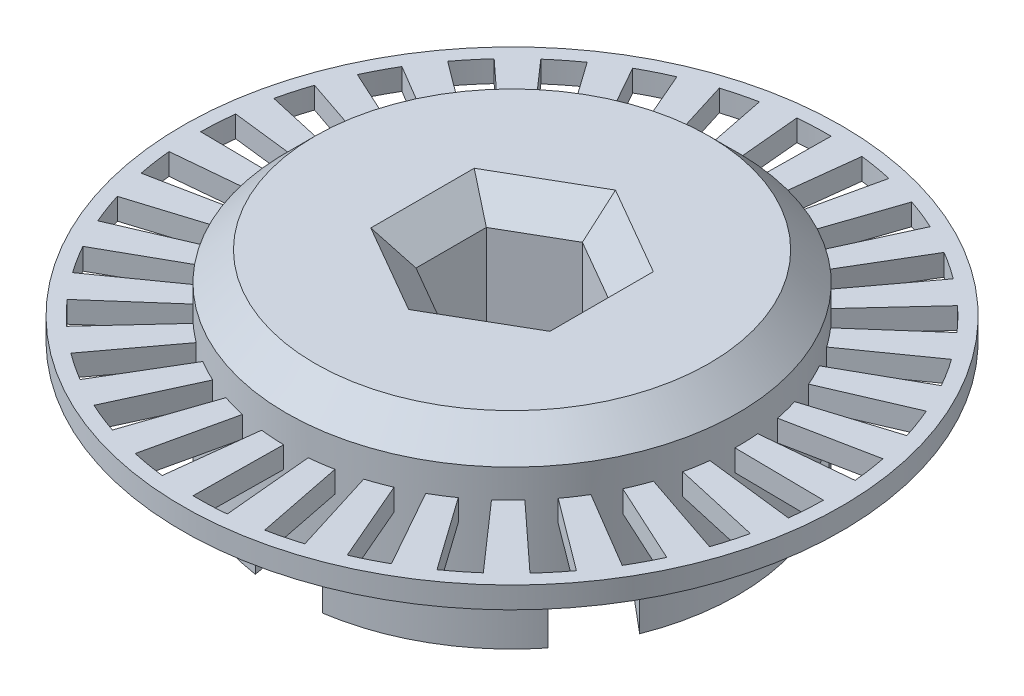
SolidWorks part; units mm, degrees
ref_plane "Front Plane" through (0, 0, 0) normal (0, 0, 1) x (1, 0, 0)
ref_plane "Top Plane" through (0, 0, 0) normal (0, 1, 0) x (1, 0, 0)
ref_plane "Right Plane" through (0, 0, 0) normal (1, 0, 0) x (0, 0, -1)
sketch "Sketch1" plane through (0, 0, 0) normal (0, 1, 0) x (1, 0, 0)
  circle A0 centre (0, 0) radius 15.75
  dimension "D1" = 31.5
extrude "Boss-Extrude1" add sketch "Sketch1" along normal blind 10
sketch "Sketch2" plane through (0, 10, 0) normal (0, 1, 0) x (1, 0, 0)
  line L0 (0, -5.5) -> (0, 5.5) construction
  line L1 (4.25, 2.4537) -> (0, 4.9075)
  line L2 (0, 4.9075) -> (-4.25, 2.4537)
  line L3 (-4.25, 2.4537) -> (-4.25, -2.4537)
  line L4 (-4.25, -2.4537) -> (0, -4.9075)
  line L5 (0, -4.9075) -> (4.25, -2.4537)
  line L6 (4.25, -2.4537) -> (4.25, 2.4537)
  circle A0 centre (0, 0) radius 4.25 construction
  dimension "D1" = 8.5
extrude "Cut-Extrude1" cut sketch "Sketch2" against normal blind 10
sketch "Sketch3" plane through (0, 0, 0) normal (0, -1, 0) x (1, 0, 0)
  line L0 (0, 0) -> (-43301.2702, -25000) construction
  line L1 (0, 0) -> (0, 50000) construction
  line L2 (0, 0) -> (43301.2702, -25000) construction
  line L3 (0, 0) -> (-50000, 0) construction
  line L4 (0, 0) -> (-7.8, 0) construction
  line L5 (-7.8, 0) -> (-38310.0222, -32139.3805) construction
  line L6 (-7.8, 0) -> (-38310.0222, 32139.3805) construction
  line L7 (-7.8, 0) -> (-14.6603, -5.7565)
  line L8 (-7.8, 0) -> (-14.6603, 5.7565)
  line L9 (-3.9, 6.755) -> (-12.3154, 9.818)
  line L10 (-3.9, 6.755) -> (-2.3449, 15.5745)
  line L11 (3.9, 6.755) -> (2.3449, 15.5745)
  line L12 (3.9, 6.755) -> (12.3154, 9.818)
  line L13 (7.8, 0) -> (14.6603, 5.7565)
  line L14 (7.8, 0) -> (14.6603, -5.7565)
  line L15 (3.9, -6.755) -> (12.3154, -9.818)
  line L16 (3.9, -6.755) -> (2.3449, -15.5745)
  line L17 (-3.9, -6.755) -> (-2.3449, -15.5745)
  line L18 (-3.9, -6.755) -> (-12.3154, -9.818)
  line L21 (5.5, 0) -> (-5.5, 0) construction
  circle A0 centre (0, 0) radius 15.75 construction
  arc A1 (-14.6603, 5.7565) -> (-14.6603, -5.7565) centre (0, 0) ccw
  arc A2 (-2.3449, 15.5745) -> (-12.3154, 9.818) centre (0, 0) ccw
  arc A3 (12.3154, 9.818) -> (2.3449, 15.5745) centre (0, 0) ccw
  arc A4 (14.6603, -5.7565) -> (14.6603, 5.7565) centre (0, 0) ccw
  arc A5 (2.3449, -15.5745) -> (12.3154, -9.818) centre (0, 0) ccw
  arc A6 (-12.3154, -9.818) -> (-2.3449, -15.5745) centre (0, 0) ccw
  point P43 (0, 0)
  circle M10 centre (0, 0) radius 15.75
  dimension "D1" = 60
  dimension "D2" = 60
  dimension "D3" = 30
  dimension "D4" = 7.8
  dimension "D5" = 40
  dimension "D6" = 40
  dimension "D7" = 6
extrude "Boss-Extrude2" add sketch "Sketch3" along normal blind 3 contours L7 L8 M10 | L17 L18 M10 | L15 L16 M10 | L13 L14 M10 | L11 L12 M10 | L9 L10 M10
sketch "Sketch4" plane through (0, 10, 0) normal (0, 1, 0) x (1, 0, 0)
  circle A0 centre (0, 0) radius 7.1
  dimension "D1" = 14.2
extrude "Cut-Extrude2" [suppressed] cut sketch "Sketch4" against normal blind 3
chamfer "Chamfer1" distance 2 angle 45 7 edges at (0, 10, 15.75) (2.125, 10, -3.6806) (-2.125, 10, -3.6806) (-4.25, 10, 0) (-2.125, 10, 3.6806) (2.125, 10, 3.6806) (4.25, 10, 0)
sketch3d "3DSketch2" plane through (0, 0, 0) normal (0, 0, 1) x (1, 0, 0)
  dimension "D1" = 6
sketch "Sketch5" plane through (0, 6, 0) normal (0, -1, 0) x (-1, 0, 0)
  line L0 (0, 0) -> (49030.2577, -9799.6852) construction
  line L1 (0, 0) -> (49786.0108, -4620.944) construction
  line L2 (0, 0) -> (49996.2981, 608.4252) construction
  line L3 (21.5733, -4.3119) -> (15.4445, -3.0869)
  line L4 (21.9058, -2.0332) -> (15.6826, -1.4556)
  line L5 (20.2054, -8.703) -> (14.4652, -6.2305)
  line L6 (21.0044, -6.5433) -> (15.0373, -4.6844)
  line L7 (17.9544, -12.7137) -> (12.8537, -9.1019)
  line L8 (19.185, -10.7673) -> (13.7347, -7.7084)
  line L9 (14.9187, -16.1688) -> (10.6805, -11.5754)
  line L10 (16.5271, -14.5208) -> (11.8319, -10.3956)
  line L11 (11.231, -18.9173) -> (8.0404, -13.5431)
  line L12 (13.1469, -17.6397) -> (9.412, -12.6284)
  line L13 (7.0525, -20.839) -> (5.0489, -14.9188)
  line L14 (9.1921, -19.9876) -> (6.5807, -14.3093)
  line L15 (2.5657, -21.8499) -> (1.8368, -15.6425)
  line L16 (4.8356, -21.462) -> (3.4618, -15.3648)
  line L17 (-2.0332, -21.9058) -> (-1.4556, -15.6826)
  line L18 (0.2677, -21.9984) -> (0.1917, -15.7488)
  line L19 (-6.5433, -21.0044) -> (-4.6844, -15.0373)
  line L20 (-4.3119, -21.5733) -> (-3.0869, -15.4445)
  line L21 (-10.7673, -19.185) -> (-7.7084, -13.7347)
  line L22 (-8.703, -20.2054) -> (-6.2305, -14.4652)
  line L23 (-14.5208, -16.5271) -> (-10.3956, -11.8319)
  line L24 (-12.7137, -17.9544) -> (-9.1019, -12.8537)
  line L25 (-17.6397, -13.1469) -> (-12.6284, -9.412)
  line L26 (-16.1688, -14.9187) -> (-11.5754, -10.6805)
  line L27 (-19.9876, -9.1921) -> (-14.3093, -6.5807)
  line L28 (-18.9173, -11.231) -> (-13.5431, -8.0404)
  line L29 (-21.462, -4.8356) -> (-15.3648, -3.4618)
  line L30 (-20.839, -7.0525) -> (-14.9188, -5.0489)
  line L31 (-21.9984, -0.2677) -> (-15.7488, -0.1917)
  line L32 (-21.8499, -2.5657) -> (-15.6425, -1.8368)
  line L33 (-21.5733, 4.3119) -> (-15.4445, 3.0869)
  line L34 (-21.9058, 2.0332) -> (-15.6826, 1.4556)
  line L35 (-20.2054, 8.703) -> (-14.4652, 6.2305)
  line L36 (-21.0044, 6.5433) -> (-15.0373, 4.6844)
  line L37 (-17.9544, 12.7137) -> (-12.8537, 9.1019)
  line L38 (-19.185, 10.7673) -> (-13.7347, 7.7084)
  line L39 (-14.9187, 16.1688) -> (-10.6805, 11.5754)
  line L40 (-16.5271, 14.5208) -> (-11.8319, 10.3956)
  line L41 (-11.231, 18.9173) -> (-8.0404, 13.5431)
  line L42 (-13.1469, 17.6397) -> (-9.412, 12.6284)
  line L43 (-7.0525, 20.839) -> (-5.0489, 14.9188)
  line L44 (-9.1921, 19.9876) -> (-6.5807, 14.3093)
  line L45 (-2.5657, 21.8499) -> (-1.8368, 15.6425)
  line L46 (-4.8356, 21.462) -> (-3.4618, 15.3648)
  line L47 (2.0332, 21.9058) -> (1.4556, 15.6826)
  line L48 (-0.2677, 21.9984) -> (-0.1917, 15.7488)
  line L49 (6.5433, 21.0044) -> (4.6844, 15.0373)
  line L50 (4.3119, 21.5733) -> (3.0869, 15.4445)
  line L51 (10.7673, 19.185) -> (7.7084, 13.7347)
  line L52 (8.703, 20.2054) -> (6.2305, 14.4652)
  line L53 (14.5208, 16.5271) -> (10.3956, 11.8319)
  line L54 (12.7137, 17.9544) -> (9.1019, 12.8537)
  line L55 (17.6397, 13.1469) -> (12.6284, 9.412)
  line L56 (16.1688, 14.9187) -> (11.5754, 10.6805)
  line L57 (19.9876, 9.1921) -> (14.3093, 6.5807)
  line L58 (18.9173, 11.231) -> (13.5431, 8.0404)
  line L59 (21.462, 4.8356) -> (15.3648, 3.4618)
  line L60 (20.839, 7.0525) -> (14.9188, 5.0489)
  line L61 (21.9984, 0.2677) -> (15.7488, 0.1917)
  line L62 (21.8499, 2.5657) -> (15.6425, 1.8368)
  circle A1 centre (0, 0) radius 23
  arc A2 (15.4445, -3.0869) -> (15.6826, -1.4556) centre (0, 0) ccw
  arc A4 (14.4652, -6.2305) -> (15.0373, -4.6844) centre (0, 0) ccw
  arc A5 (20.2054, -8.703) -> (21.0044, -6.5433) centre (0, 0) ccw
  arc A6 (21.5733, -4.3119) -> (21.9058, -2.0332) centre (0, 0) ccw
  arc A7 (12.8537, -9.1019) -> (13.7347, -7.7084) centre (0, 0) ccw
  arc A8 (17.9544, -12.7137) -> (19.185, -10.7673) centre (0, 0) ccw
  arc A9 (10.6805, -11.5754) -> (11.8319, -10.3956) centre (0, 0) ccw
  arc A10 (14.9187, -16.1688) -> (16.5271, -14.5208) centre (0, 0) ccw
  arc A11 (8.0404, -13.5431) -> (9.412, -12.6284) centre (0, 0) ccw
  arc A12 (11.231, -18.9173) -> (13.1469, -17.6397) centre (0, 0) ccw
  arc A13 (5.0489, -14.9188) -> (6.5807, -14.3093) centre (0, 0) ccw
  arc A14 (7.0525, -20.839) -> (9.1921, -19.9876) centre (0, 0) ccw
  arc A15 (1.8368, -15.6425) -> (3.4618, -15.3648) centre (0, 0) ccw
  arc A16 (2.5657, -21.8499) -> (4.8356, -21.462) centre (0, 0) ccw
  arc A17 (-1.4556, -15.6826) -> (0.1917, -15.7488) centre (0, 0) ccw
  arc A18 (-2.0332, -21.9058) -> (0.2677, -21.9984) centre (0, 0) ccw
  arc A19 (-4.6844, -15.0373) -> (-3.0869, -15.4445) centre (0, 0) ccw
  arc A20 (-6.5433, -21.0044) -> (-4.3119, -21.5733) centre (0, 0) ccw
  arc A21 (-7.7084, -13.7347) -> (-6.2305, -14.4652) centre (0, 0) ccw
  arc A22 (-10.7673, -19.185) -> (-8.703, -20.2054) centre (0, 0) ccw
  arc A23 (-10.3956, -11.8319) -> (-9.1019, -12.8537) centre (0, 0) ccw
  arc A24 (-14.5208, -16.5271) -> (-12.7137, -17.9544) centre (0, 0) ccw
  arc A25 (-12.6284, -9.412) -> (-11.5754, -10.6805) centre (0, 0) ccw
  arc A26 (-17.6397, -13.1469) -> (-16.1688, -14.9187) centre (0, 0) ccw
  arc A27 (-14.3093, -6.5807) -> (-13.5431, -8.0404) centre (0, 0) ccw
  arc A28 (-19.9876, -9.1921) -> (-18.9173, -11.231) centre (0, 0) ccw
  arc A29 (-15.3648, -3.4618) -> (-14.9188, -5.0489) centre (0, 0) ccw
  arc A30 (-21.462, -4.8356) -> (-20.839, -7.0525) centre (0, 0) ccw
  arc A31 (-15.7488, -0.1917) -> (-15.6425, -1.8368) centre (0, 0) ccw
  arc A32 (-21.9984, -0.2677) -> (-21.8499, -2.5657) centre (0, 0) ccw
  arc A33 (-15.4445, 3.0869) -> (-15.6826, 1.4556) centre (0, 0) ccw
  arc A34 (-21.5733, 4.3119) -> (-21.9058, 2.0332) centre (0, 0) ccw
  arc A35 (-14.4652, 6.2305) -> (-15.0373, 4.6844) centre (0, 0) ccw
  arc A36 (-20.2054, 8.703) -> (-21.0044, 6.5433) centre (0, 0) ccw
  arc A37 (-12.8537, 9.1019) -> (-13.7347, 7.7084) centre (0, 0) ccw
  arc A38 (-17.9544, 12.7137) -> (-19.185, 10.7673) centre (0, 0) ccw
  arc A39 (-10.6805, 11.5754) -> (-11.8319, 10.3956) centre (0, 0) ccw
  arc A40 (-14.9187, 16.1688) -> (-16.5271, 14.5208) centre (0, 0) ccw
  arc A41 (-8.0404, 13.5431) -> (-9.412, 12.6284) centre (0, 0) ccw
  arc A42 (-11.231, 18.9173) -> (-13.1469, 17.6397) centre (0, 0) ccw
  arc A43 (-5.0489, 14.9188) -> (-6.5807, 14.3093) centre (0, 0) ccw
  arc A44 (-7.0525, 20.839) -> (-9.1921, 19.9876) centre (0, 0) ccw
  arc A45 (-1.8368, 15.6425) -> (-3.4618, 15.3648) centre (0, 0) ccw
  arc A46 (-2.5657, 21.8499) -> (-4.8356, 21.462) centre (0, 0) ccw
  arc A47 (1.4556, 15.6826) -> (-0.1917, 15.7488) centre (0, 0) ccw
  arc A48 (2.0332, 21.9058) -> (-0.2677, 21.9984) centre (0, 0) ccw
  arc A49 (4.6844, 15.0373) -> (3.0869, 15.4445) centre (0, 0) ccw
  arc A50 (6.5433, 21.0044) -> (4.3119, 21.5733) centre (0, 0) ccw
  arc A51 (7.7084, 13.7347) -> (6.2305, 14.4652) centre (0, 0) ccw
  arc A52 (10.7673, 19.185) -> (8.703, 20.2054) centre (0, 0) ccw
  arc A53 (10.3956, 11.8319) -> (9.1019, 12.8537) centre (0, 0) ccw
  arc A54 (14.5208, 16.5271) -> (12.7137, 17.9544) centre (0, 0) ccw
  arc A55 (12.6284, 9.412) -> (11.5754, 10.6805) centre (0, 0) ccw
  arc A56 (17.6397, 13.1469) -> (16.1688, 14.9187) centre (0, 0) ccw
  arc A57 (14.3093, 6.5807) -> (13.5431, 8.0404) centre (0, 0) ccw
  arc A58 (19.9876, 9.1921) -> (18.9173, 11.231) centre (0, 0) ccw
  arc A59 (15.3648, 3.4618) -> (14.9188, 5.0489) centre (0, 0) ccw
  arc A60 (21.462, 4.8356) -> (20.839, 7.0525) centre (0, 0) ccw
  arc A61 (15.7488, 0.1917) -> (15.6425, 1.8368) centre (0, 0) ccw
  arc A62 (21.9984, 0.2677) -> (21.8499, 2.5657) centre (0, 0) ccw
  circle A63 centre (0, 0) radius 13.75
  circle A64 centre (0, 0) radius 13.75 construction
  point P134 (0, 0)
  dimension "D3" = 30
  dimension "D5" = 1
  dimension "D4" = 46
  dimension "D6" = 0
  dimension "D1" = 6
  dimension "D2" = 6
extrude "Boss-Extrude3" add sketch "Sketch5" along normal blind 1.5
